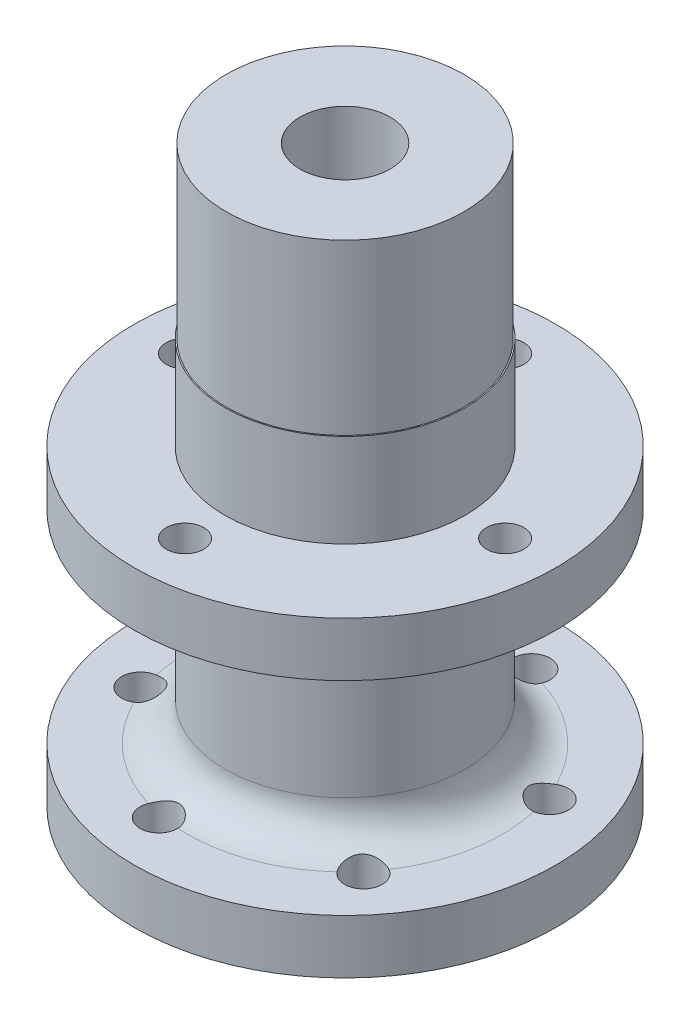
SolidWorks part; units mm, degrees
ref_plane "Piano frontale" through (0, 0, 0) normal (0, 0, 1) x (1, 0, 0)
ref_plane "Piano superiore" through (0, 0, 0) normal (0, 1, 0) x (1, 0, 0)
ref_plane "Piano destro" through (0, 0, 0) normal (1, 0, 0) x (0, 0, -1)
sketch "Schizzo1" plane through (0, 0, 0) normal (0, 1, 0) x (1, 0, 0)
  circle A0 centre (0, 0) radius 14.03
  dimension "D1" = 28.06
extrude "Estrusione-Estrusione1" add sketch "Schizzo1" along normal blind 3.6
sketch "Schizzo2" plane through (0, 3.6, 0) normal (0, 1, 0) x (1, 0, 0)
  circle A0 centre (0, 0) radius 7.98
  dimension "D1" = 15.96
extrude "Estrusione-Estrusione2" add sketch "Schizzo2" along normal blind 13.53
sketch "Schizzo3" plane through (0, 17.13, 0) normal (0, 1, 0) x (1, 0, 0)
  circle A0 centre (0, 0) radius 14.03 construction
  circle A1 centre (0, 0) radius 14.03
extrude "Estrusione-Estrusione3" add sketch "Schizzo3" along normal blind 3.6
sketch "Schizzo4" plane through (0, 20.73, 0) normal (0, 1, 0) x (1, 0, 0)
  circle A0 centre (0, 0) radius 7.995
  dimension "D1" = 15.99
extrude "Estrusione-Estrusione4" add sketch "Schizzo4" along normal blind 6.2
sketch "Schizzo5" plane through (0, 0, 0) normal (0, -1, 0) x (1, 0, 0)
  circle A0 centre (0, 0) radius 7.995
  dimension "D1" = 15.99
extrude "Estrusione-Estrusione5" add sketch "Schizzo5" along normal blind 1.95
sketch "Schizzo6" plane through (0, 26.93, 0) normal (0, 1, 0) x (1, 0, 0)
  circle A0 centre (0, 0) radius 7.915
  dimension "D1" = 15.83
extrude "Estrusione-Estrusione6" add sketch "Schizzo6" along normal blind 11.25
fillet "Raccordo1" radius 2.5 2 edges at (0, 3.6, 7.98) (0, 17.13, 7.98)
hole_wizard "Foro filettato M3x0.5-1" positions "Schizzo9" profile "Schizzo8" tap size "M3x0.5" standard "Ansi Metric"
sketch "Schizzo9" plane through (0, 20.73, 0) normal (0, 1, 0) x (1, 0, 0)
  circle A1 centre (0, 0) radius 10.65
  point P0 (0, 10.65)
  point P2 (10.65, 0)
  point P4 (-10.65, 0)
  point P6 (0, -10.65)
  dimension "D1" = 21.3
cosmetic thread "Filettatura del foro1" parameters "D1"=3.8453, "D2"=3
cosmetic thread "Filettatura del foro2" parameters "D1"=3.8453, "D2"=3
cosmetic thread "Filettatura del foro3" parameters "D1"=3.8453, "D2"=3
cosmetic thread "Filettatura del foro4" parameters "D1"=3.8453, "D2"=3
sketch "Schizzo8" plane through (0, 20.73, -10.65) normal (1, 0, 0) x (0, 0, 1)
  line L0 (0, 0) -> (0, 6.8511)
  line L1 (0, 6.8511) -> (1.25, 6.1)
  line L2 (1.25, 6.1) -> (1.25, 0)
  line L5 (1.25, 0) -> (0, 0)
  line L10 (0, 6.8511) -> (-1.25, 6.1) construction
  line L11 (0, -6.35) -> (0, 107.95) construction
  dimension "Tap Drill Dia." = 2.5
  dimension "Tap Drill Depth" = 6.1
  dimension "Drill Angle" = 118
sketch "Schizzo10" plane through (0, 38.18, 0) normal (0, 1, 0) x (1, 0, 0)
  circle A0 centre (0, 0) radius 3
  dimension "D1" = 6
extrude "Taglio-Estrusione1" cut sketch "Schizzo10" against normal through all
hole_wizard "Foro filettato M3x0.5-2" positions "Schizzo12" profile "Schizzo11" tap size "M3x0.5" standard "Ansi Metric"
sketch "Schizzo12" plane through (0, 0, 0) normal (0, -1, 0) x (-1, 0, 0)
  circle A0 centre (0, 0) radius 10.65
  point P0 (-10.0301, 3.5804)
  point P12 (-1.9144, 10.4765)
  point P13 (8.1158, 6.8962)
  point P14 (10.0301, -3.5804)
  point P15 (1.9144, -10.4765)
  point P16 (-8.1158, -6.8962)
  point P17 (0, 0)
  dimension "D1" = 21.3
  dimension "D2" = 6
sketch "Schizzo11" plane through (10.0301, 0, -3.5804) normal (1, 0, 0) x (0, 0, -1)
  line L0 (0, 0) -> (0, 9.2511)
  line L1 (0, 9.2511) -> (1.25, 8.5)
  line L2 (1.25, 8.5) -> (1.25, 0)
  line L5 (1.25, 0) -> (0, 0)
  line L10 (0, 9.2511) -> (-1.25, 8.5) construction
  line L11 (0, -6.35) -> (0, 107.95) construction
  dimension "Tap Drill Dia." = 2.5
  dimension "Tap Drill Depth" = 8.5
  dimension "Drill Angle" = 118
cosmetic thread "Filettatura del foro17" parameters "D1"=3.8453, "D2"=3
cosmetic thread "Filettatura del foro18" parameters "D1"=3.8453, "D2"=3
cosmetic thread "Filettatura del foro19" parameters "D1"=3.8453, "D2"=3
cosmetic thread "Filettatura del foro20" parameters "D1"=3.8453, "D2"=3
cosmetic thread "Filettatura del foro21" parameters "D1"=3.8453, "D2"=3
cosmetic thread "Filettatura del foro22" parameters "D1"=3.8453, "D2"=3
